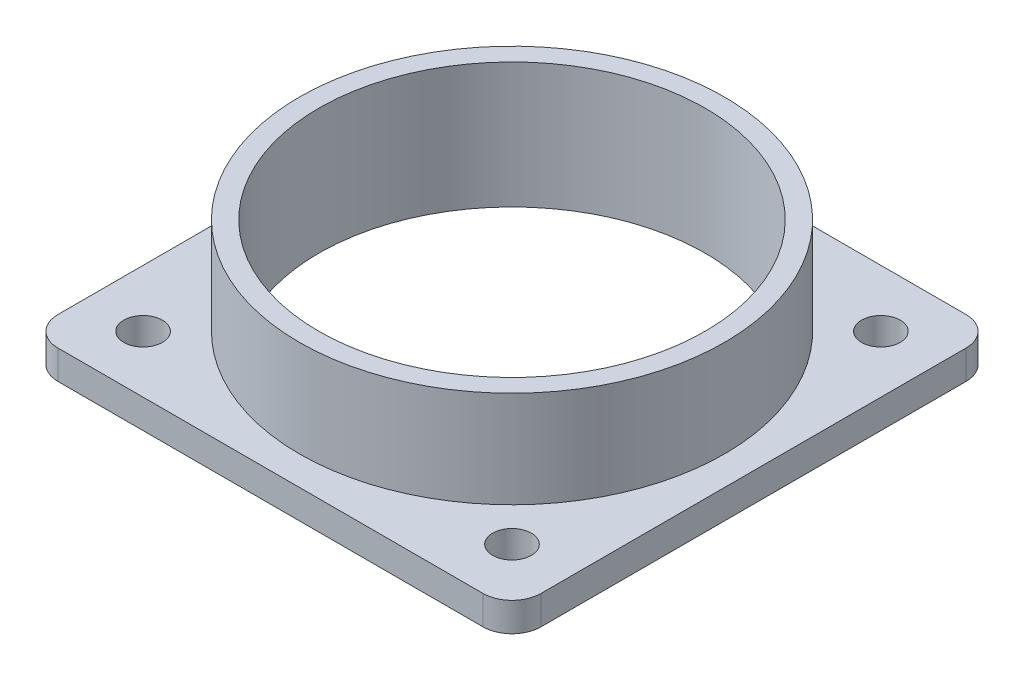
SolidWorks part; units mm, degrees
ref_plane "Спереди" through (0, 0, 0) normal (0, 0, 1) x (1, 0, 0)
ref_plane "Сверху" through (0, 0, 0) normal (0, 1, 0) x (1, 0, 0)
ref_plane "Справа" through (0, 0, 0) normal (1, 0, 0) x (0, 0, -1)
sketch "Sketch1" plane through (0, 0, 0) normal (0, 1, 0) x (1, 0, 0)
  line L1 (0, 25) -> (-25, 25)
  line L2 (-25, 25) -> (-25, -25)
  line L3 (-25, -25) -> (25, -25)
  line L4 (25, -25) -> (25, 25)
  line L5 (25, 25) -> (0, 25)
  circle A1 centre (-19.0919, 19.0919) radius 2
  circle A2 centre (19.0919, 19.0919) radius 2
  circle A3 centre (19.0919, -19.0919) radius 2
  circle A4 centre (-19.0919, -19.0919) radius 2
  circle A10 centre (0, 0) radius 20
  point P8 (-19.0919, 19.0919)
  point P21 (0, 0)
  dimension "D1" = 4
extrude "Boss-Extrude1" add sketch "Sketch1" along normal blind 3
fillet "Fillet2" radius 3 4 edges at (25, 1.5, -25) (25, 1.5, 25) (-25, 1.5, 25) (-25, 1.5, -25)
sketch "Sketch2" plane through (0, 3, 0) normal (0, 1, 0) x (1, 0, 0)
  circle A0 centre (0, 0) radius 22
  circle A1 centre (0, 0) radius 20
extrude "Boss-Extrude3" add sketch "Sketch2" along normal blind 10
